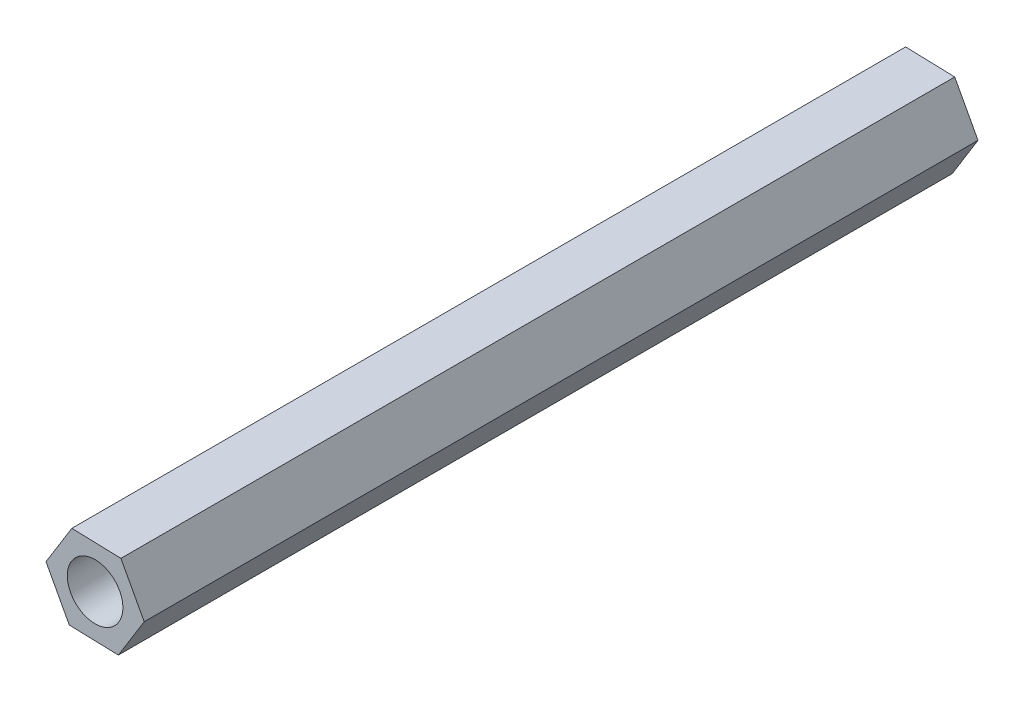
SolidWorks part; units mm, degrees
ref_plane "Front Plane" through (0, 0, 0) normal (0, 0, 1) x (1, 0, 0)
ref_plane "Top Plane" through (0, 0, 0) normal (0, 1, 0) x (1, 0, 0)
ref_plane "Right Plane" through (0, 0, 0) normal (1, 0, 0) x (0, 0, -1)
sketch "Sketch1" plane through (0, 0, 0) normal (0, 0, 1) x (1, 0, 0)
  line L1 (1.256, -2.3348) -> (2.65, -0.0797)
  line L2 (2.65, -0.0797) -> (1.394, 2.2551)
  line L3 (1.394, 2.2551) -> (-1.256, 2.3348)
  line L4 (-1.256, 2.3348) -> (-2.65, 0.0797)
  line L5 (-2.65, 0.0797) -> (-1.394, -2.2551)
  line L6 (-1.394, -2.2551) -> (1.256, -2.3348)
  circle A0 centre (0, 0) radius 2.296 construction
  circle A1 centre (0, 0) radius 1.5
  dimension "D2" = 3
  dimension "D1" = 5.3
extrude "Boss-Extrude1" add sketch "Sketch1" along normal blind 45
